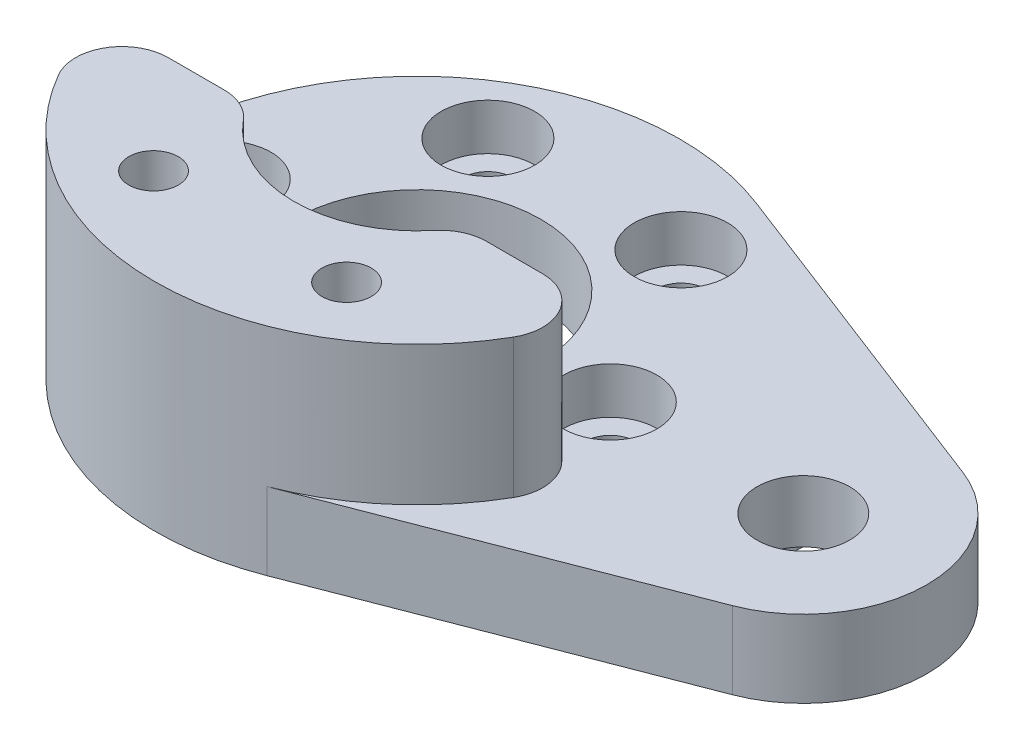
SolidWorks part; units mm, degrees
ref_plane "Спереди" through (0, 0, 0) normal (0, 0, 1) x (1, 0, 0)
ref_plane "Сверху" through (0, 0, 0) normal (0, 1, 0) x (1, 0, 0)
ref_plane "Справа" through (0, 0, 0) normal (1, 0, 0) x (0, 0, -1)
ref_plane "Плоскость4" through (0, 0, 0) normal (0, -1, 0) x (1, 0, 0)
sketch "Эскиз1" plane through (0, 0, 0) normal (0, -1, 0) x (1, 0, 0)
  line L0 (6.12, -15.8602) -> (27.88, -7.4636)
  line L1 (27.88, 7.4636) -> (6.12, 15.8602)
  arc A0 (6.12, 15.8602) -> (6.12, -15.8602) centre (0, 0) ccw
  arc A1 (27.88, -7.4636) -> (27.88, 7.4636) centre (25, 0) ccw
extrude "Бобышка-Вытянуть1" add sketch "Эскиз1" against normal blind 5
sketch "Эскиз2" plane through (0, 5, 0) normal (0, 1, 0) x (-1, 0, 0)
  line L0 (12.1244, 4) -> (-12.1244, 4)
  arc A0 (-12.1244, 4) -> (-14.7224, 8.5) centre (-12.1244, 7) cw
  arc A1 (-14.7224, 8.5) -> (14.7224, 8.5) centre (0, 0) cw
  arc A2 (14.7224, 8.5) -> (12.1244, 4) centre (12.1244, 7) cw
extrude "Бобышка-Вытянуть2" add sketch "Эскиз2" along normal blind 9
sketch "Эскиз3" plane through (0, 0, 0) normal (0, -1, 0) x (1, 0, 0)
  line L0 (21.85, 3.883) -> (21.85, -3.883)
  line L1 (28.15, -3.883) -> (28.15, 3.883)
  arc A0 (28.15, 3.883) -> (21.85, 3.883) centre (25, 0) ccw
  arc A1 (21.85, -3.883) -> (28.15, -3.883) centre (25, 0) ccw
extrude "Вырез-Вытянуть1" cut sketch "Эскиз3" against normal blind 1
hole_wizard "Диаметр отверстия Ø3.0 (3)1" positions "Эскиз5" profile "Эскиз4" hole size "Ø3.0" standard "Ansi Metric"
sketch "Эскиз5" plane through (0, 0, 0) normal (0, -1, 0) x (-1, 0, 0)
  point P0 (0, 12.5)
sketch "Эскиз4" plane through (0, 0, -12.5) normal (1, 0, 0) x (0, 0, -1)
  line L0 (0, 0) -> (0, 4.4013)
  line L1 (0, 4.4013) -> (1.5, 3.5)
  line L2 (1.5, 3.5) -> (1.5, 0)
  line L5 (1.5, 0) -> (0, 0)
  line L10 (0, 4.4013) -> (-1.5, 3.5) construction
  line L11 (0, -6.35) -> (0, 107.95) construction
  dimension "Диаметр отверстия" = 3
  dimension "Глубина отверстия" = 3.5
  dimension "Угол заточки сверла" = 118
hole_wizard "Диаметр отверстия Ø3.0 (3)2" positions "Эскиз7" profile "Эскиз6" hole size "Ø3.0" standard "Ansi Metric"
sketch "Эскиз7" plane through (0, 0, 0) normal (0, -1, 0) x (-1, 0, 0)
  point P0 (0, -12.5)
sketch "Эскиз6" plane through (0, 0, 12.5) normal (1, 0, 0) x (0, 0, -1)
  line L0 (0, 0) -> (0, 4.4013)
  line L1 (0, 4.4013) -> (1.5, 3.5)
  line L2 (1.5, 3.5) -> (1.5, 0)
  line L5 (1.5, 0) -> (0, 0)
  line L10 (0, 4.4013) -> (-1.5, 3.5) construction
  line L11 (0, -6.35) -> (0, 107.95) construction
  dimension "Диаметр отверстия" = 3
  dimension "Глубина отверстия" = 3.5
  dimension "Угол заточки сверла" = 118
hole_wizard "Цековка для винта с заклепочной головкой M31" positions "Эскиз9" profile "Эскиз8" counterbore size "M3" standard "Ansi Metric"
sketch "Эскиз9" plane through (0, 5, 0) normal (0, 1, 0) x (1, 0, 0)
  point P0 (12.5, 0)
  point P1 (6.25, 10.8253)
  point P2 (-6.25, 10.8253)
  point P3 (-12.5, 0)
sketch "Эскиз8" plane through (12.5, 5, 0) normal (1, 0, 0) x (0, 0, 1)
  line L0 (0, 0) -> (0, 5)
  line L1 (0, 5) -> (1.6, 5)
  line L3 (1.6, 5) -> (1.6, 3)
  line L4 (1.6, 3) -> (3.025, 3)
  line L5 (3.025, 3) -> (3.025, 0)
  line L7 (3.025, 0) -> (0, 0)
  line L11 (0, -6.35) -> (0, 107.95) construction
  dimension "Диаметр сквозного отверстия" = 3.2
  dimension "Глубина сквозного отверстия" = 5
  dimension "Диаметр цековки" = 6.05
  dimension "Глубина цековки" = 3
hole_wizard "Диаметр отверстия Ø16.0 (16)1" positions "Эскиз11" profile "Эскиз10" hole size "Ø16.0" standard "Ansi Metric"
sketch "Эскиз11" plane through (0, 0, 0) normal (0, -1, 0) x (-1, 0, 0)
  point P0 (0, 0)
sketch "Эскиз10" plane through (0, 0, 0) normal (1, 0, 0) x (0, 0, -1)
  line L0 (0, 0) -> (0, 14)
  line L1 (0, 14) -> (8, 14)
  line L2 (8, 14) -> (8, 0)
  line L5 (8, 0) -> (0, 0)
  line L11 (0, -6.35) -> (0, 107.95) construction
  dimension "Диаметр сквозного отверстия" = 16
  dimension "Глубина сквозного отверстия" = 14
hole_wizard "Диаметр отверстия Ø3.2 (3.2)1" positions "Эскиз13" profile "Эскиз12" hole size "Ø3.2" standard "Ansi Metric"
sketch "Эскиз13" plane through (0, 0, 0) normal (0, -1, 0) x (-1, 0, 0)
  point P0 (6.25, -10.8253)
  point P1 (-6.25, -10.8253)
sketch "Эскиз12" plane through (-6.25, 0, 10.8253) normal (1, 0, 0) x (0, 0, -1)
  line L0 (0, 0) -> (0, 14)
  line L1 (0, 14) -> (1.6, 14)
  line L2 (1.6, 14) -> (1.6, 0)
  line L5 (1.6, 0) -> (0, 0)
  line L11 (0, -6.35) -> (0, 107.95) construction
  dimension "Диаметр сквозного отверстия" = 3.2
  dimension "Глубина сквозного отверстия" = 14
hole_wizard "Диаметр отверстия Ø6.0 (6)1" positions "Эскиз15" profile "Эскиз14" hole size "Ø6.0" standard "Ansi Metric"
sketch "Эскиз15" plane through (0, 1, 0) normal (0, -1, 0) x (-1, 0, 0)
  point P0 (-25, 0)
sketch "Эскиз14" plane through (25, 1, 0) normal (1, 0, 0) x (0, 0, -1)
  line L0 (0, 0) -> (0, 13)
  line L1 (0, 13) -> (3, 13)
  line L2 (3, 13) -> (3, 0)
  line L5 (3, 0) -> (0, 0)
  line L11 (0, -6.35) -> (0, 107.95) construction
  dimension "Диаметр сквозного отверстия" = 6
  dimension "Глубина сквозного отверстия" = 13
fillet "Скругление1" radius 2 4 edges at (28.15, 0.5, -3.883) (28.15, 0.5, 3.883) (21.85, 0.5, 3.883) (21.85, 0.5, -3.883)
fillet "Скругление2" radius 3 2 edges at (6.9282, 9.5, 4) (-6.9282, 9.5, 4)
